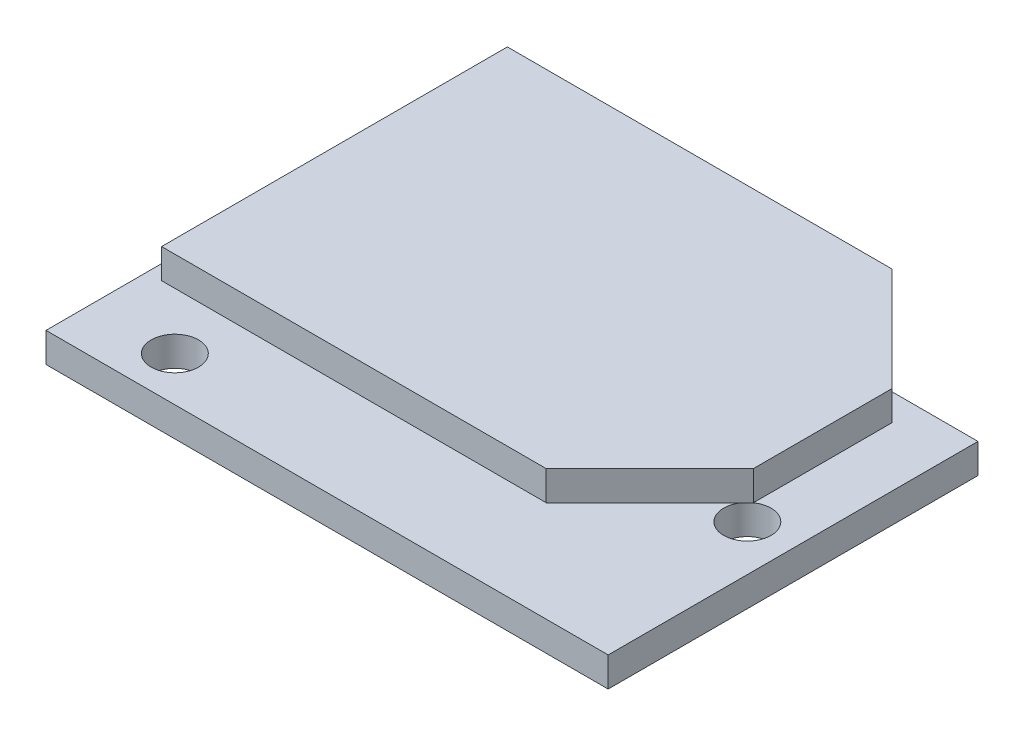
SolidWorks part; units mm, degrees
ref_plane "Ebene vorne" through (0, 0, 0) normal (0, 0, 1) x (1, 0, 0)
ref_plane "Ebene oben" through (0, 0, 0) normal (0, 1, 0) x (1, 0, 0)
ref_plane "Ebene rechts" through (0, 0, 0) normal (1, 0, 0) x (0, 0, -1)
sketch "Sketch1" plane through (0, 0, 0) normal (0, 1, 0) x (1, 0, 0)
  line L0 (-10.3687, 0) -> (25.2304, 0) construction
  line L2 (0, 12.5) -> (38, 12.5)
  line L3 (0, 12.5) -> (0, -12.5)
  line L4 (0, -12.5) -> (38, -12.5)
  line L5 (38, 12.5) -> (38, -12.5)
  circle A0 centre (5.71, 9.5) radius 1.6
  circle A1 centre (5.71, -9.5) radius 1.6
  circle A2 centre (34.91, 0) radius 1.6
  dimension "D4" = 3.2
  dimension "D5" = 3.2
  dimension "D1" = 25
  dimension "D2" = 38
  dimension "D3" = 19
  dimension "D6" = 5.71
  dimension "D7" = 29.2
extrude "Boss-Extrude1" add sketch "Sketch1" along normal blind 2
sketch "Sketch2" plane through (0, 2, 0) normal (0, 1, 0) x (1, 0, 0)
  line L0 (33, -11.6864) -> (40, -4.6864)
  line L1 (7, 11.6864) -> (33, 11.6864)
  line L2 (7, 11.6864) -> (7, -11.6864)
  line L3 (7, -11.6864) -> (33, -11.6864)
  line L4 (3.4909, 0) -> (48.4454, 0) construction
  line L5 (40, -4.6864) -> (40, 4.6864)
  line L6 (40, 4.6864) -> (33, 11.6864)
  line L7 (0, 12.5) -> (0, -12.5) construction
  line L8 (38, -12.5) -> (38, 12.5) construction
  point P9 (0, 0)
  dimension "D1" = 45
  dimension "D2" = 26
  dimension "D3" = 7
  dimension "D4" = 2
  dimension "D5" = 45
extrude "Boss-Extrude2" add sketch "Sketch2" along normal blind 2 from offset 6 separate body
